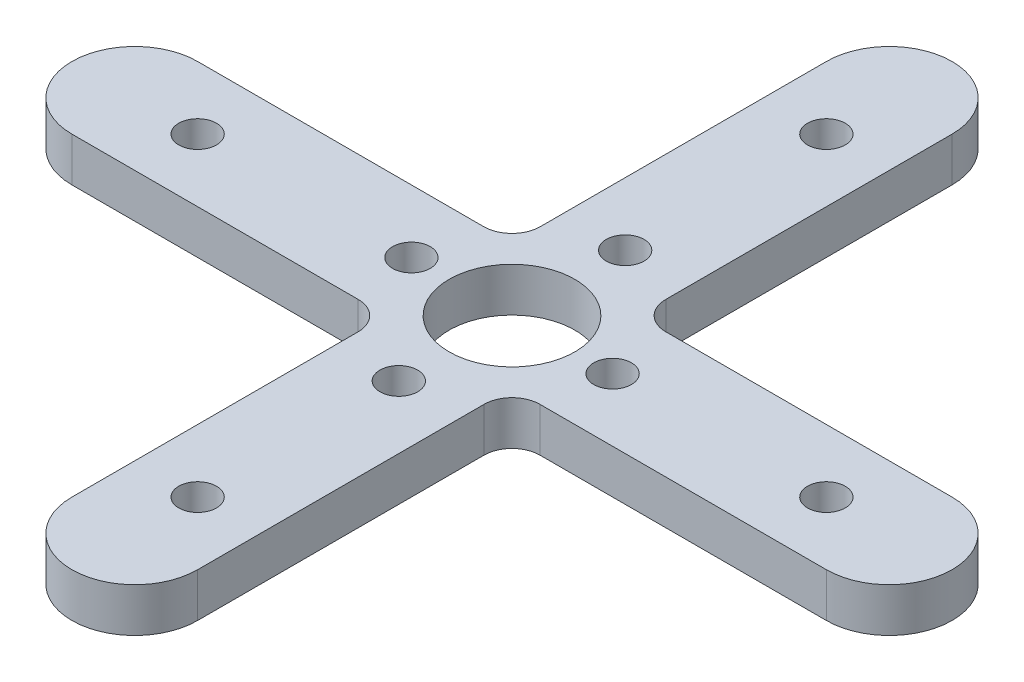
SolidWorks part; units mm, degrees
ref_plane "Alzado" through (0, 0, 0) normal (0, 0, 1) x (1, 0, 0)
ref_plane "Planta" through (0, 0, 0) normal (0, 1, 0) x (1, 0, 0)
ref_plane "Vista lateral" through (0, 0, 0) normal (1, 0, 0) x (0, 0, -1)
sketch "Croquis1" plane through (0, 0, 0) normal (0, 1, 0) x (1, 0, 0)
  line L0 (1.4757, 3.6958) -> (1.4757, 11.4846)
  line L6 (11.4757, 26.4535) -> (11.4757, 3.6555)
  line L7 (13.6977, 1.4535) -> (36.4757, 1.4535)
  line L15 (-23.5243, 1.4535) -> (-0.7665, 1.4535)
  line L16 (1.4757, -10.7887) -> (1.4757, -18.5775)
  line L17 (6.4757, -3.5465) -> (6.4757, 5.4535) construction
  line L18 (1.4757, -10.7887) -> (1.4757, -33.5465)
  line L19 (13.6977, -8.5465) -> (36.4757, -8.5465)
  line L20 (1.4757, 3.6958) -> (1.4757, 26.4535)
  line L21 (11.4757, -33.5465) -> (11.4757, -10.7484)
  line L22 (1.4757, -8.5775) -> (1.4757, -8.5465)
  line L23 (11.4757, -10.7484) -> (11.4757, -10.7887)
  line L24 (1.4757, -8.5465) -> (1.4757, -8.5775)
  line L25 (-23.5243, -8.5465) -> (-0.7665, -8.5465)
  line L26 (6.4757, -3.5465) -> (11.4757, -3.5465) construction
  line L29 (-17.0243, -3.5465) -> (-18.5243, -3.5465) construction
  line L30 (-0.0243, -3.5465) -> (-3.0243, -3.5465) construction
  line L31 (12.9757, -3.5465) -> (15.9757, -3.5465) construction
  circle A1 centre (6.4757, -3.5465) radius 5
  arc A2 (-0.7665, 1.4535) -> (1.4757, 3.6958) centre (-0.7665, 3.6958) ccw
  arc A4 (11.4757, -10.7484) -> (11.4757, -10.7887) centre (13.6977, -10.7685) ccw
  arc A5 (11.4757, 3.6958) -> (13.6977, 1.4535) centre (13.6977, 3.6756) ccw
  arc A6 (-23.5243, 1.4535) -> (-23.5243, -8.5465) centre (-23.5243, -3.5465) ccw
  arc A7 (36.4757, -8.5465) -> (36.4757, 1.4535) centre (36.4757, -3.5465) ccw
  arc A9 (11.4757, 26.4535) -> (1.4757, 26.4535) centre (6.4757, 26.4535) ccw
  arc A10 (11.4757, -10.7887) -> (13.6977, -8.5465) centre (13.6977, -10.7685) cw
  arc A11 (-0.7665, -8.5465) -> (1.4757, -10.7887) centre (-0.7665, -10.7887) cw
  arc A12 (1.4757, -33.5465) -> (11.4757, -33.5465) centre (6.4757, -33.5465) ccw
  circle A13 centre (-1.5243, -3.5465) radius 1.5
  circle A14 centre (14.4757, -3.5465) radius 1.5
  circle A15 centre (-18.5243, -3.5465) radius 1.5
  circle A16 centre (6.4757, 21.4535) radius 1.5
  circle A17 centre (31.4757, -3.5465) radius 1.5
  circle A18 centre (6.4757, -28.5465) radius 1.5
  circle A19 centre (6.4757, -12.5465) radius 1.5
  circle A20 centre (6.4757, 5.4535) radius 1.5
  point P0 (0, 0)
  dimension "D11" = 10
  dimension "D5" = 3
  dimension "D6" = 3
  dimension "D8" = 3
  dimension "D13" = 3
  dimension "D14" = 3
  dimension "D15" = 3
  dimension "D17" = 3
  dimension "D19" = 3
  dimension "D2" = 8
  dimension "D3" = 10
  dimension "D4" = 8
  dimension "D7" = 25
  dimension "D9" = 25
  dimension "D10" = 25
  dimension "D12" = 25
  dimension "D16" = 9
  dimension "D18" = 9
extrude "Saliente-Extruir2" add sketch "Croquis1" along normal blind 3.5
